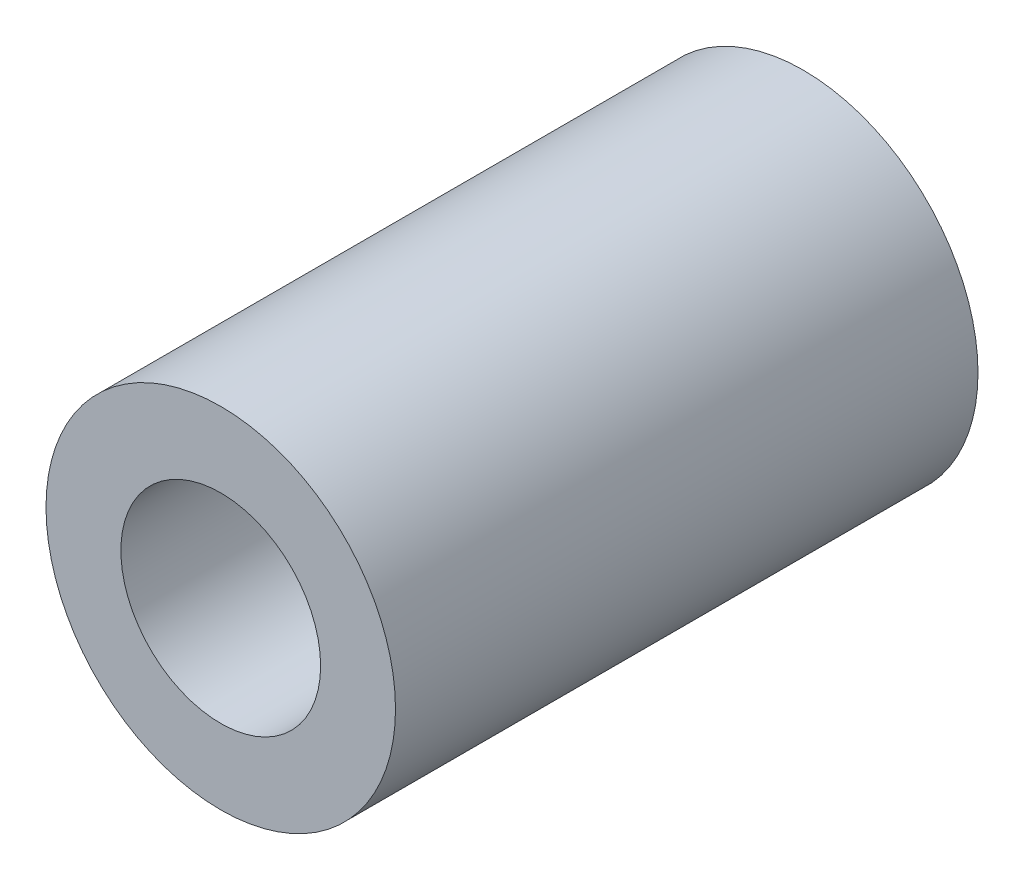
SolidWorks part; units mm, degrees
ref_plane "Front" through (0, 0, 0) normal (0, 0, 1) x (1, 0, 0)
ref_plane "Top" through (0, 0, 0) normal (0, 1, 0) x (1, 0, 0)
ref_plane "Right" through (0, 0, 0) normal (1, 0, 0) x (0, 0, -1)
sketch "Sketch1" plane through (0, 0, 0) normal (0, 0, 1) x (1, 0, 0)
  circle A0 centre (0, 0) radius 6
  circle A1 centre (0, 0) radius 3.429
  dimension "D1" = 12
  dimension "D2" = 6.858
extrude "Boss-Extrude1" add sketch "Sketch1" along normal mid plane 20
